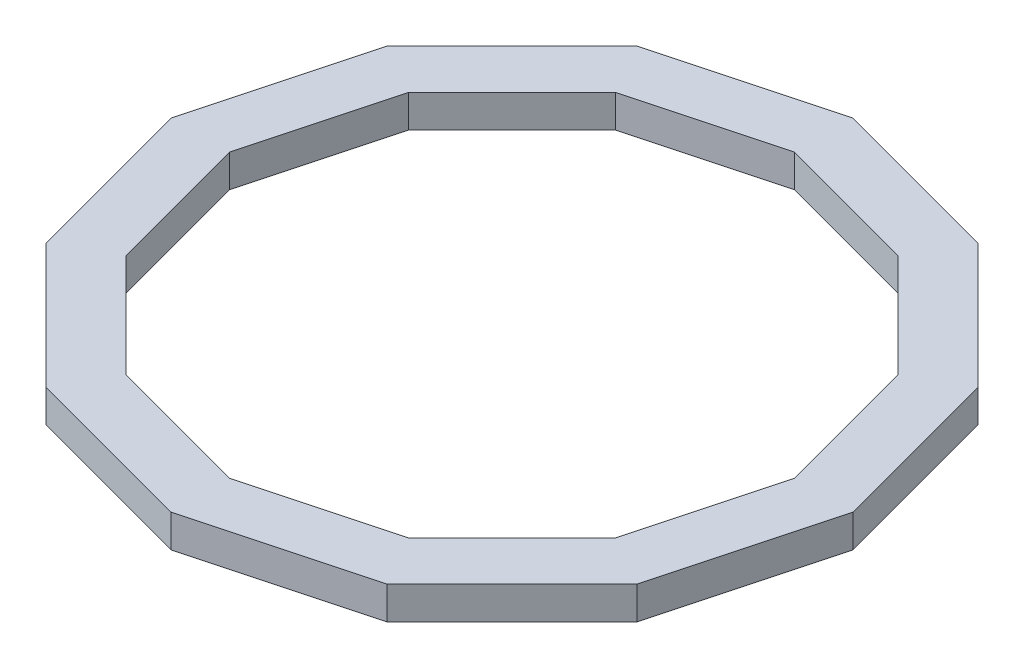
SolidWorks part; units mm, degrees
ref_plane "Front Plane" through (0, 0, 0) normal (0, 0, 1) x (1, 0, 0)
ref_plane "Top Plane" through (0, 0, 0) normal (0, 1, 0) x (1, 0, 0)
ref_plane "Right Plane" through (0, 0, 0) normal (1, 0, 0) x (0, 0, -1)
sketch "Sketch2" plane through (0, 0, 0) normal (0, 1, 0) x (1, 0, 0)
  line L1 (-198.7296, 0) -> (-172.1049, -99.3648)
  line L2 (-172.1049, -99.3648) -> (-99.3648, -172.1049)
  line L3 (-99.3648, -172.1049) -> (0, -198.7296)
  line L4 (0, -198.7296) -> (99.3648, -172.1049)
  line L5 (99.3648, -172.1049) -> (172.1049, -99.3648)
  line L6 (172.1049, -99.3648) -> (198.7296, 0)
  line L7 (198.7296, 0) -> (172.1049, 99.3648)
  line L8 (172.1049, 99.3648) -> (99.3648, 172.1049)
  line L9 (99.3648, 172.1049) -> (0, 198.7296)
  line L10 (0, 198.7296) -> (-99.3648, 172.1049)
  line L11 (-99.3648, 172.1049) -> (-172.1049, 99.3648)
  line L12 (-172.1049, 99.3648) -> (-198.7296, 0)
  line L13 (-164.5448, 0) -> (-142.4999, -82.2724)
  line L14 (-142.4999, -82.2724) -> (-82.2724, -142.4999)
  line L15 (-82.2724, -142.4999) -> (0, -164.5448)
  line L16 (0, -164.5448) -> (82.2724, -142.4999)
  line L17 (82.2724, -142.4999) -> (142.4999, -82.2724)
  line L18 (142.4999, -82.2724) -> (164.5448, 0)
  line L19 (164.5448, 0) -> (142.4999, 82.2724)
  line L20 (142.4999, 82.2724) -> (82.2724, 142.4999)
  line L21 (82.2724, 142.4999) -> (0, 164.5448)
  line L22 (0, 164.5448) -> (-82.2724, 142.4999)
  line L23 (-82.2724, 142.4999) -> (-142.4999, 82.2724)
  line L24 (-142.4999, 82.2724) -> (-164.5448, 0)
  circle A0 centre (0, 0) radius 191.958 construction
  circle A1 centre (0, 0) radius 158.938 construction
  dimension "D1" = 102.87
  dimension "D2" = 33.02
extrude "Boss-Extrude2" add sketch "Sketch2" along normal blind 19.05 separate body
